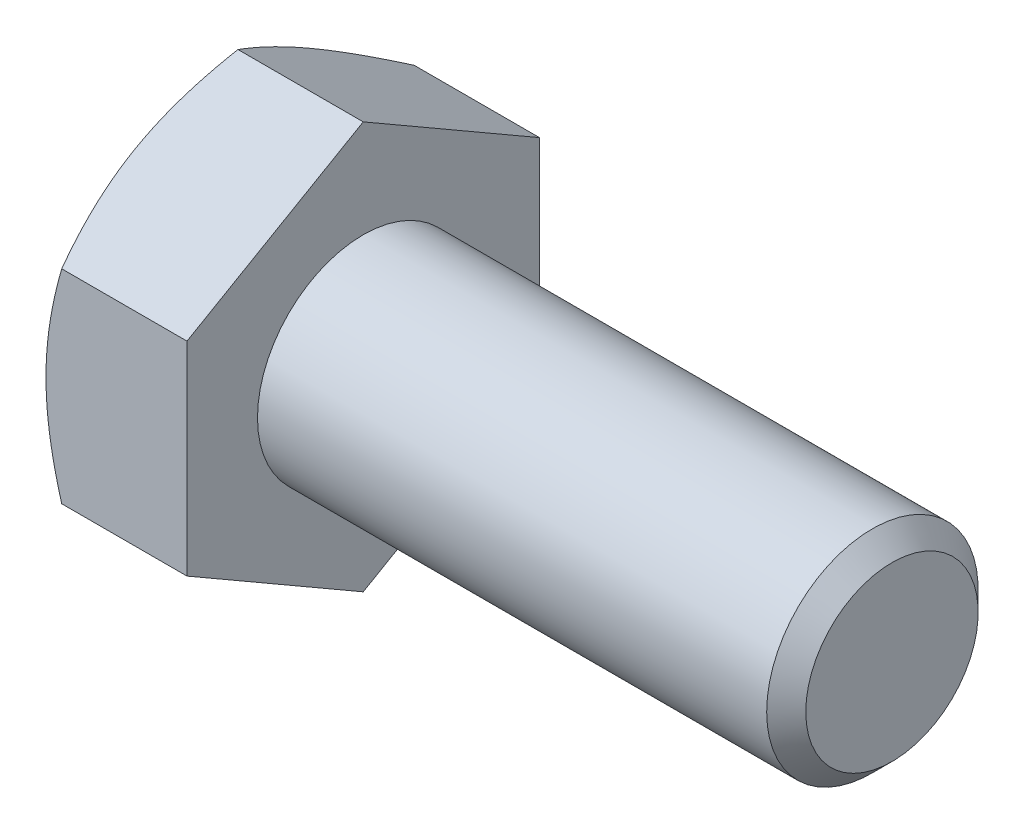
SolidWorks part; units mm, degrees
extrude "BaseHead" add sketch "Sketch1" along normal blind 4
sketch "Sketch1" plane through (0, 0, 0) normal (1, 0, 0) x (0, 0, -1)
  line L0 (5, 2.8868) -> (5, -2.8868)
  line L1 (-5, 2.8868) -> (-5, -2.8868)
  line L2 (5, -2.8868) -> (0, -5.7735)
  line L3 (0, -5.7735) -> (-5, -2.8868)
  line L4 (5, 2.8868) -> (0, 5.7735)
  line L5 (0, 5.7735) -> (-5, 2.8868)
  dimension "Width_flats" = 10
  dimension "D2" = 120
  dimension "D3" = 5
  dimension "D4" = 5
  dimension "D5" = 5
ref_plane "Plane1" through (0, 0, 0) normal (0, 0, 1) x (1, 0, 0)
ref_plane "Plane2" through (0, 0, 0) normal (0, 1, 0) x (1, 0, 0)
ref_plane "Plane3" through (0, 0, 0) normal (1, 0, 0) x (0, 0, -1)
sketch "BodySke" plane through (0, 0, 0) normal (0, 0, 1) x (1, 0, 0)
  line L1 (0, 0) -> (19, 0)
  line L2 (0, 0) -> (0, 3)
  line L4 (19, 0) -> (19, 2.4455)
  line L5 (4, 5.7735) -> (4, 2.8868) construction
  line L6 (19, 2.4455) -> (18.4455, 3)
  line L7 (0, 0) -> (110.49, 0) construction
  line L8 (19, -2.4455) -> (18.4455, -3) construction
  line L9 (0, 2.8868) -> (0, -2.8868) construction
  line L10 (5, 15.24) -> (5, -1.27) construction
  line L11 (1, 15.24) -> (1, -1.27) construction
  line L12 (4, 2.8868) -> (4, -2.8868) construction
  line L15 (0, 3) -> (18.4455, 3)
  dimension "Body_ch_ang" = 45
  dimension "Minor_dia" = 4.891
  dimension "Diameter" = 6
  dimension "Advance" = 1
revolve "BaseBody" add sketch "BodySke" angle 360 about L7
cosmetic thread "ThreadCosmetic" [suppressed] parameters "Thread_length"=14, "Thread_minor"=4.891
fillet "HeadFillet" [suppressed] radius 0.25
sketch "Sketch3" plane through (0, 0, 0) normal (0, 0, 1) x (1, 0, 0)
  line L0 (0, 5) -> (3.3333, 10.7735)
  line L1 (0, 5.7735) -> (0, 2.8868) construction
  line L2 (3.3333, 10.7735) -> (3.3333, 15.7735)
  line L3 (3.3333, 15.7735) -> (-10, 15.7735)
  line L4 (-10, 15.7735) -> (-10, 5)
  line L5 (-10, 5) -> (0, 5)
  line L6 (0, 0) -> (99.06, 0) construction
  line L7 (4, 5.7735) -> (0, 5.7735) construction
  dimension "D4" = 5
  dimension "D1" = 5
  dimension "D2" = 5
  dimension "D3" = 10
  dimension "Head_ch_ang" = 30
revolve "HeadChamfer" cut sketch "Sketch3" angle 360 about L6
sketch "ThdSchSke" plane through (0, 0, 0) normal (0, 0, 1) x (1, 0, 0)
  line L0 (5, -2.4455) -> (4.6117, -3)
  line L1 (5, -2.4455) -> (5.3883, -3)
  line L2 (5.3883, -3) -> (5.3883, -3.75)
  line L3 (-3.175, 0) -> (5.1513, 0) construction
  line L5 (5.3883, -3.75) -> (4.6117, -3.75)
  line L6 (4.6117, -3.75) -> (4.6117, -3)
  dimension "Thread_minor" = 4.891
  dimension "Diameter" = 6
  dimension "Start" = 5
revolve "ThreadSchematic" [suppressed] cut sketch "ThdSchSke" angle 360 about L3
pattern_linear "ThdSchPat" [suppressed]
equation "\"D3@Sketch1\" = \"Width_flats@Sketch1\" / 2"
equation "\"D4@Sketch1\" = \"D3@Sketch1\""
equation "\"D5@Sketch1\" = \"D4@Sketch1\""
equation "\"Thread_minor@ThreadCosmetic\" = \"Minor_dia@BodySke\""
equation "\"D1@Sketch3\" = \"Width_flats@Sketch1\" / 2"
equation "\"Thread_length@ThreadCosmetic\" = ((sgn( (\"Length@BodySke\" - \"Advance@BodySke\" ) - \"Thread_nom@BodySke\" )-1)*( (\"Length@BodySke\" - \"Advance@BodySke\" ) - \"Thread_nom@BodySke\" ))/-2+ \"Thread_nom@BodySke\""
equation "\"Thread_minor@ThdSchSke\" = \"Minor_dia@BodySke\""
equation "\"Diameter@ThdSchSke\" = \"Diameter@BodySke\""
equation "\"Overcut@ThdSchSke\" = \"Diameter@BodySke\" * 1.25"
equation "\"Start@ThdSchSke\" = \"Head_ht@BaseHead\" + \"Length@BodySke\" - \"Thread_length@ThreadCosmetic\"  '---Non-countersunk---"
equation "\"Num_threads@ThdSchPat\" = int( \"Thread_length@ThreadCosmetic\" / \"Advance@BodySke\" + 0.999 )  + 1"
equation "\"Advance@ThdSchPat\" = \"Thread_length@ThreadCosmetic\" /  (\"Num_threads@ThdSchPat\" - 1) 'relax it"
equation "\"Num_threads@ThdSchPat\" = \"Num_threads@ThdSchPat\" - sgn( \"Num_threads@ThdSchPat\" - 1) '---chamfered tips only---"
